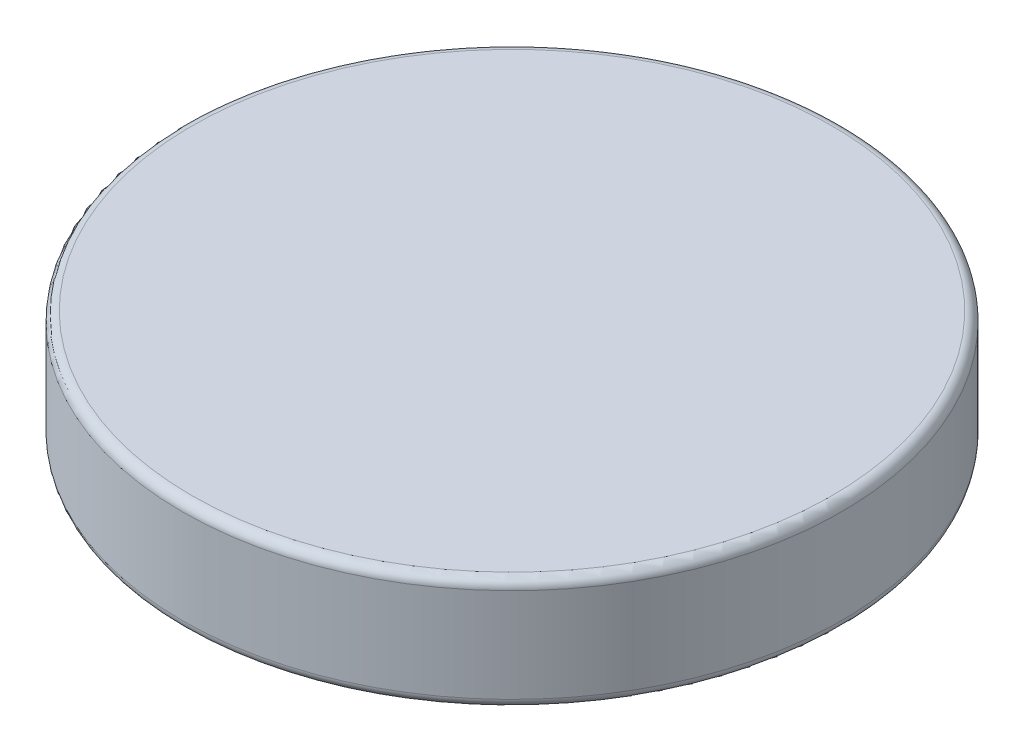
SolidWorks part; units mm, degrees
ref_plane "前视基准面" through (0, 0, 0) normal (0, 0, 1) x (1, 0, 0)
ref_plane "上视基准面" through (0, 0, 0) normal (0, 1, 0) x (1, 0, 0)
ref_plane "右视基准面" through (0, 0, 0) normal (1, 0, 0) x (0, 0, -1)
sketch "草图1" plane through (0, 0, 0) normal (0, 1, 0) x (1, 0, 0)
  circle A0 centre (0, 0) radius 35
  dimension "D1" = 70
extrude "凸台-拉伸1" add sketch "草图1" along normal blind 12
fillet "圆角1" radius 1 2 edges at (0, 0, 35) (0, 12, 35)
